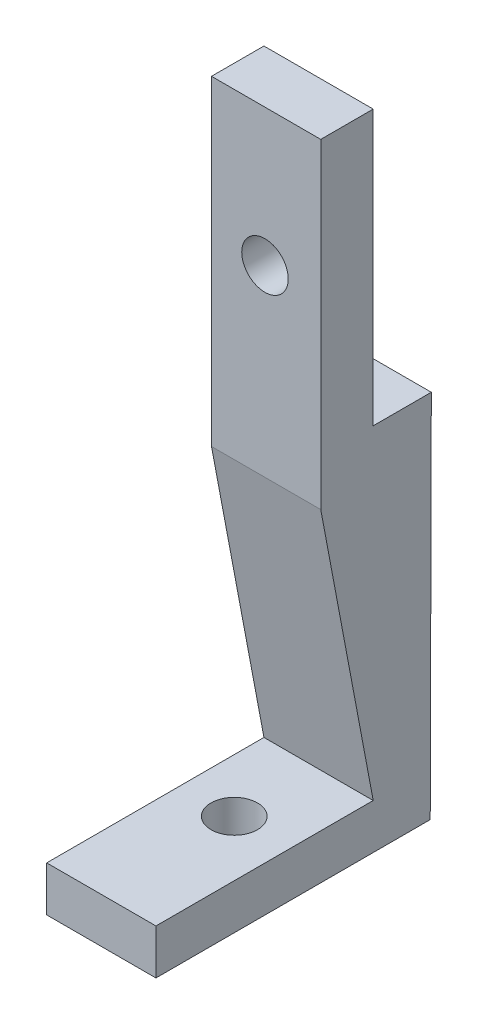
SolidWorks part; units mm, degrees
ref_plane "Front Plane" through (0, 0, 0) normal (0, 0, 1) x (1, 0, 0)
ref_plane "Top Plane" through (0, 0, 0) normal (0, 1, 0) x (1, 0, 0)
ref_plane "Right Plane" through (0, 0, 0) normal (1, 0, 0) x (0, 0, -1)
sketch "Sketch1" plane through (0, 0, 0) normal (1, 0, 0) x (0, 0, -1)
  line L0 (-2.4535, 27.7) -> (-2.4535, 15.9)
  line L1 (-2.4535, 15.9) -> (0.0465, 15.9)
  line L2 (0.0465, 15.9) -> (0, 0)
  line L3 (0, 0) -> (-11.8, 0)
  line L4 (-11.8, 0) -> (-11.8, 1.9395)
  line L5 (-11.8, 1.9395) -> (-2.4535, 1.9395)
  line L6 (-4.7098, 13.9091) -> (-4.7098, 27.7)
  line L7 (-4.7098, 27.7) -> (-2.4535, 27.7)
  line L8 (-4.7098, 13.9091) -> (-2.4535, 1.9395)
extrude "Boss-Extrude1" add sketch "Sketch1" along normal blind 4.7
sketch "Sketch2" plane through (0, 0, 2.4535) normal (0, 0, -1) x (-1, 0, 0)
  circle A0 centre (-2.3, 21.8) radius 1
  dimension "D1" = 2
extrude "Cut-Extrude1" cut sketch "Sketch2" against normal blind 4.7
sketch "Sketch3" plane through (0, 0, 0) normal (0, -1, 0) x (1, 0, 0)
  circle A0 centre (2.3, 6.031) radius 1
  dimension "D1" = 2
extrude "Cut-Extrude2" cut sketch "Sketch3" against normal blind 4.7
